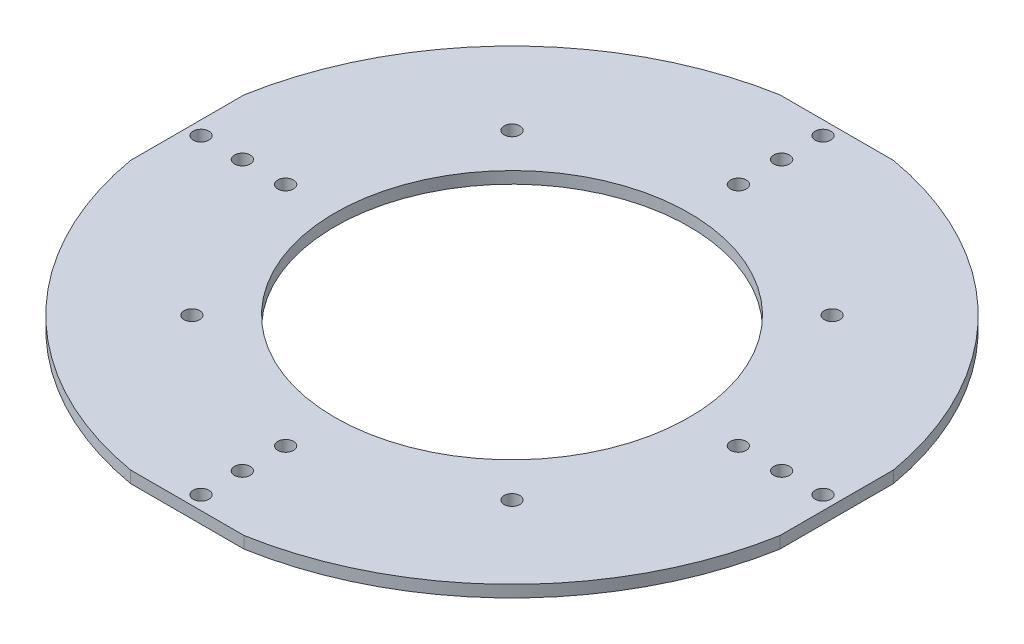
SolidWorks part; units mm, degrees
material "7075-T6 (SN)"
ref_plane "Front Plane" through (0, 0, 0) normal (0, 0, 1) x (1, 0, 0)
ref_plane "Top Plane" through (0, 0, 0) normal (0, 1, 0) x (1, 0, 0)
ref_plane "Right Plane" through (0, 0, 0) normal (1, 0, 0) x (0, 0, -1)
sketch "Sketch1" plane through (0, 0, 0) normal (0, 1, 0) x (1, 0, 0)
  line L0 (0, -137) -> (0, -158) construction
  line L1 (-167.5, -167.5) -> (167.5, -167.5) construction
  line L6 (-167.5, -167.5) -> (-167.5, 167.5) construction
  line L7 (-167.5, 167.5) -> (167.5, 167.5) construction
  line L9 (167.5, -167.5) -> (167.5, 167.5) construction
  line L10 (-167.5, -167.5) -> (167.5, 167.5) construction
  line L12 (-167.5, 167.5) -> (167.5, -167.5) construction
  line L15 (-165, -165) -> (165, -165) construction
  line L16 (-165, -165) -> (-165, 165) construction
  line L17 (-165, 165) -> (165, 165) construction
  line L18 (165, -165) -> (165, 165) construction
  line L19 (-165, -165) -> (165, 165) construction
  line L20 (-165, 165) -> (165, -165) construction
  circle A1 centre (0, 115) radius 4
  circle A2 centre (0, 0) radius 90
  circle A6 centre (0, 115) radius 12.5 construction
  circle A11 centre (-137, 0) radius 4
  circle A12 centre (-158, 0) radius 4
  circle A13 centre (0, -158) radius 4
  circle A14 centre (0, -137) radius 4
  circle A17 centre (81.3173, 81.3173) radius 4
  circle A18 centre (115, 0) radius 4
  circle A19 centre (81.3173, -81.3173) radius 4
  circle A20 centre (0, -115) radius 4
  circle A21 centre (-81.3173, -81.3173) radius 4
  circle A22 centre (-115, 0) radius 4
  circle A23 centre (-81.3173, 81.3173) radius 4
  circle A28 centre (0, 137) radius 4
  circle A29 centre (0, 158) radius 4
  circle A30 centre (137, 0) radius 4
  circle A31 centre (158, 0) radius 4
  circle A32 centre (167.5, 167.5) radius 10.5 construction
  circle A33 centre (167.5, -167.5) radius 10.5 construction
  circle A34 centre (-167.5, -167.5) radius 10.5 construction
  circle A35 centre (-167.5, 167.5) radius 10.5 construction
  circle A36 centre (0, 0) radius 167.5
  point P5 (0, 0)
  point P6 (0, 0)
  point P12 (0, 0)
  point P73 (0, 0)
  dimension "D2" = 8
  dimension "D4" = 180
  dimension "D6" = 25
  dimension "D7" = 330
  dimension "D8" = 330
  dimension "D9" = 7
  dimension "D11" = 335
  dimension "D13" = 21
  dimension "D15" = 335
  dimension "D3" = 115
  dimension "D5" = 4
  dimension "D10" = 21
  dimension "D12" = 335
  dimension "D14" = 4
extrude "Boss-Extrude1" add sketch "Sketch1" along normal blind 6
sketch "Sketch4" plane through (0, 6, 0) normal (0, 1, 0) x (1, 0, 0)
  line L1 (-165, -165) -> (165, -165)
  line L2 (-165, -165) -> (-165, 165)
  line L3 (-165, 165) -> (165, 165)
  line L4 (165, -165) -> (165, 165)
  line L5 (-165, -165) -> (165, 165) construction
  line L6 (-165, 165) -> (165, -165) construction
  point P0 (0, 0)
  dimension "D1" = 330
  dimension "D2" = 330
extrude "Cut-Extrude3" cut sketch "Sketch4" against normal blind 10 flip side to cut
sketch "Sketch5" plane through (0, 6, 0) normal (0, 1, 0) x (1, 0, 0)
  line L0 (-81.3173, -81.3173) -> (-236.8808, -236.8808) construction
  dimension "D1" = 220
